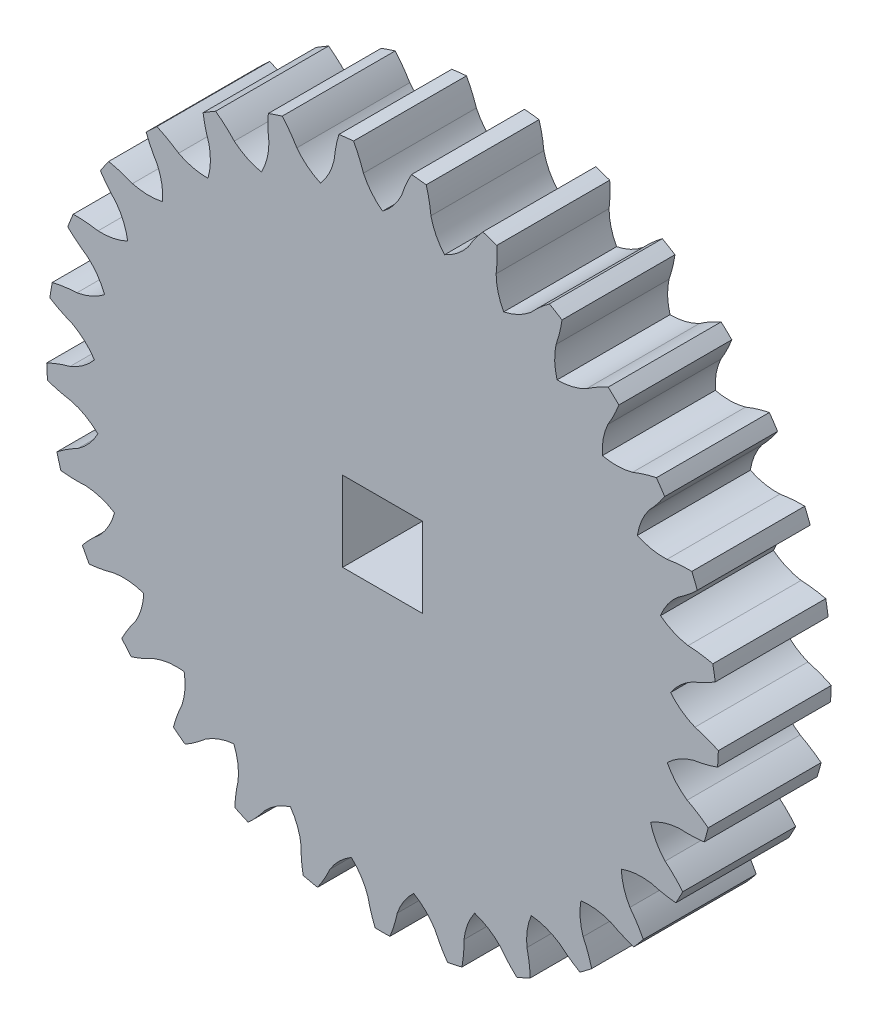
SolidWorks part; units mm, degrees
ref_plane "Front Plane" through (0, 0, 0) normal (0, 0, 1) x (1, 0, 0)
ref_plane "Top Plane" through (0, 0, 0) normal (0, 1, 0) x (1, 0, 0)
ref_plane "Right Plane" through (0, 0, 0) normal (1, 0, 0) x (0, 0, -1)
sketch "Sketch1" plane through (0, 0, 0) normal (0, 0, 1) x (1, 0, 0)
  line L1 (3.5355, -3.5355) -> (-3.5355, -3.5355)
  line L2 (3.5355, -3.5355) -> (3.5355, 3.5355)
  line L3 (3.5355, 3.5355) -> (-3.5355, 3.5355)
  line L4 (-3.5355, -3.5355) -> (-3.5355, 3.5355)
  line L5 (3.5355, -3.5355) -> (-3.5355, 3.5355) construction
  line L6 (3.5355, 3.5355) -> (-3.5355, -3.5355) construction
  circle A0 centre (0, 0) radius 29.75
  circle A1 centre (0, 0) radius 5 construction
  dimension "D1" = 59.5
  dimension "D2" = 10
extrude "Boss-Extrude1" add sketch "Sketch1" along normal blind 10
sketch "Sketch2" plane through (0, 0, 0) normal (0, 0, 1) x (1, 0, 0)
  line L0 (0, 0) -> (0, 36.6661) construction
  arc A25 (0, 25.5436) -> (-1.6909, 27.6123) centre (3.2409, 29.9179) cw
  arc A26 (-1.6909, 27.6123) -> (-6.9218, 34.1) centre (-12.7926, 24.0138) ccw
  arc A27 (-6.9218, 34.1) -> (0, 36.6661) centre (0.5436, 24.5815) cw
  arc A28 (6.9218, 34.1) -> (0, 36.6661) centre (-0.5436, 24.5815) ccw
  arc A29 (1.6909, 27.6123) -> (6.9218, 34.1) centre (12.7926, 24.0138) cw
  arc A30 (0, 25.5436) -> (1.6909, 27.6123) centre (-3.2409, 29.9179) ccw
extrude "Cut-Extrude1" cut sketch "Sketch2" along normal through all
pattern_circular "CirPattern1" count 29 over 360 about axis through (0, 0, 0) along (0, 0, 1) of "Cut-Extrude1"
sketch "Sketch3" plane through (0, 0, 0) normal (0, 0, 1) x (1, 0, 0)
  circle A0 centre (0, 0) radius 29.75
  dimension "D1" = 59.5
